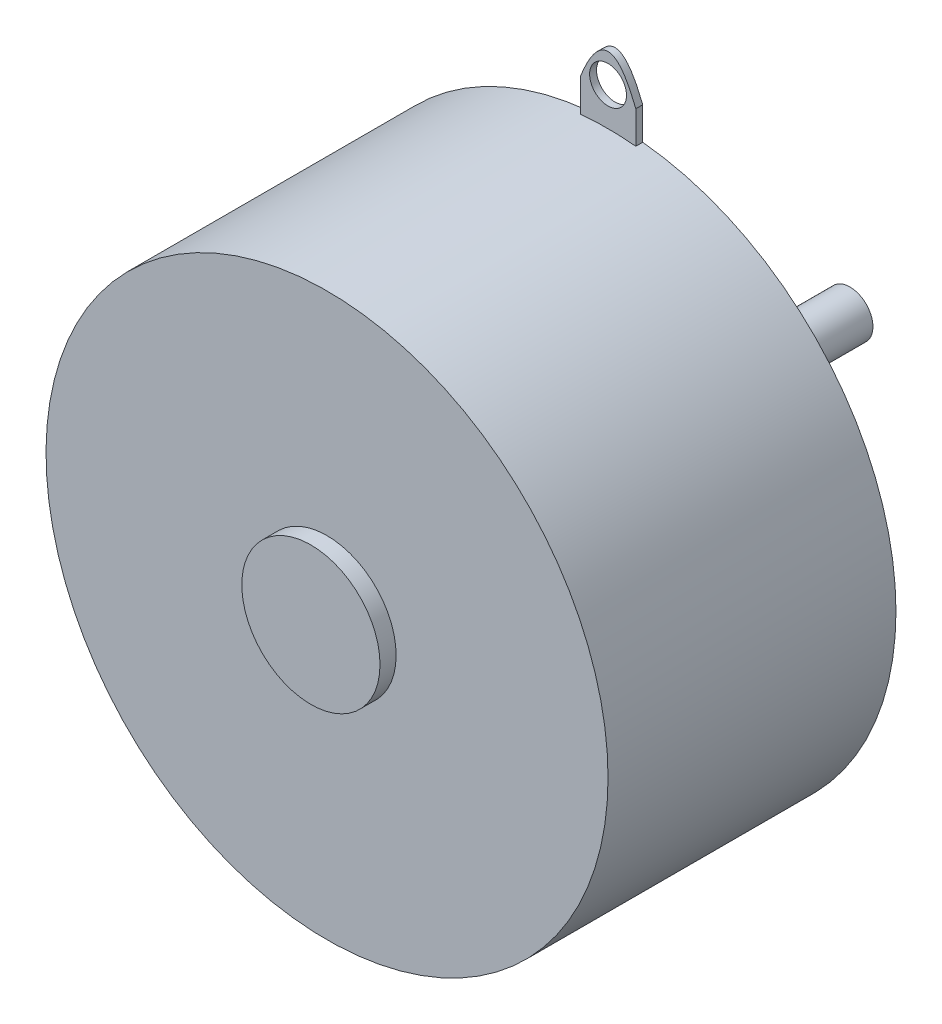
SolidWorks part; units mm, degrees
material "1060 合金"
ref_plane "前视基准面" through (0, 0, 0) normal (0, 0, 1) x (1, 0, 0)
ref_plane "上视基准面" through (0, 0, 0) normal (0, 1, 0) x (1, 0, 0)
ref_plane "右视基准面" through (0, 0, 0) normal (1, 0, 0) x (0, 0, -1)
sketch "草图1" plane through (0, 0, 0) normal (0, 0, 1) x (1, 0, 0)
  circle A0 centre (0, 0) radius 12.2
  dimension "D1" = 24.4
extrude "凸台-拉伸1" add sketch "草图1" along normal blind 12.5
sketch "草图2" plane through (0, 0, 12.5) normal (0, 0, 1) x (1, 0, 0)
  circle A0 centre (0, 0) radius 3
  dimension "D1" = 6
extrude "凸台-拉伸2" add sketch "草图2" along normal blind 0.7
sketch "草图3" plane through (0, 0, 0) normal (0, 0, -1) x (-1, 0, 0)
  circle A0 centre (0, 0) radius 3.25
  dimension "D1" = 6.5
extrude "凸台-拉伸3" add sketch "草图3" along normal blind 1
sketch "草图4" plane through (0, 0, -1) normal (0, 0, -1) x (-1, 0, 0)
  circle A0 centre (0, 0) radius 1
  dimension "D1" = 2
extrude "凸台-拉伸4" add sketch "草图4" along normal blind 9.2
sketch "草图5" plane through (0, 0, 0) normal (0, 0, -1) x (-1, 0, 0)
  circle A0 centre (0, 0) radius 8.25 construction
  circle A1 centre (0, 8.25) radius 0.85
  circle A2 centre (7.1447, 4.125) radius 0.85
  circle A3 centre (7.1447, -4.125) radius 0.85
  circle A4 centre (0, -8.25) radius 0.85
  circle A5 centre (-7.1447, -4.125) radius 0.85
  circle A6 centre (-7.1447, 4.125) radius 0.85
  point P17 (0, 0)
  dimension "D1" = 16.5
  dimension "D2" = 1.7
  dimension "D3" = 6
extrude "切除-拉伸1" cut sketch "草图5" against normal blind 0.35 contours A1 | A6 | A5 | A4 | A3 | A2
sketch "草图9" plane through (0, 0, 0) normal (0, 0, -1) x (-1, 0, 0)
  line L0 (0, 0) -> (1.899, 0)
  line L1 (-1.2057, 12.1403) -> (-1.2057, 13.5503)
  line L2 (1.2057, 12.1403) -> (1.2057, 13.5503)
  line L3 (1.2057, -12.1403) -> (1.2057, -13.5503)
  line L4 (-1.2057, -12.1403) -> (-1.2057, -13.5503)
  circle A0 centre (0, 0) radius 12.2 construction
  circle A1 centre (0, 13.85) radius 0.8
  circle A2 centre (0, -13.85) radius 0.8
  spline S0 degree 2 poles (-1.2057, 13.5503) (0, 16.6469) (1.2057, 13.5503) knots 0 0 0 1 1 1
  spline S1 degree 2 poles (-1.2057, 12.1403) (0, 12.2597) (1.2057, 12.1403) knots 0 0 0 1 1 1
  spline S2 degree 2 poles (-1.2057, -12.1403) (0, -12.2597) (1.2057, -12.1403) knots 0 0 0 1 1 1
  spline S3 degree 2 poles (-1.2057, -13.5503) (0, -16.6469) (1.2057, -13.5503) knots 0 0 0 1 1 1
  circle M15 centre (0, 0) radius 12.2
extrude "凸台-拉伸7" add sketch "草图9" against normal blind 0.3 contours S0 L1 L2 A1 M15 | L4 S3 L3 A2 M15
sketch "草图10" plane through (0, 0, -1) normal (0, 0, -1) x (-1, 0, 0)
  circle A0 centre (0, 0) radius 1
  circle A1 centre (0, 0) radius 3.25
extrude "切除-拉伸3" cut sketch "草图10" against normal blind 0.5
extrude "切除-拉伸4" cut sketch "草图11" against normal blind 0.2 and the other way blind 2
sketch "草图11" plane through (-21.215, -62.2547, -57.1763) normal (0.9559, -0.2937, 0) x (0, 0, 1)
  circle A0 centre (49.8426, -65.698) radius 0.3
